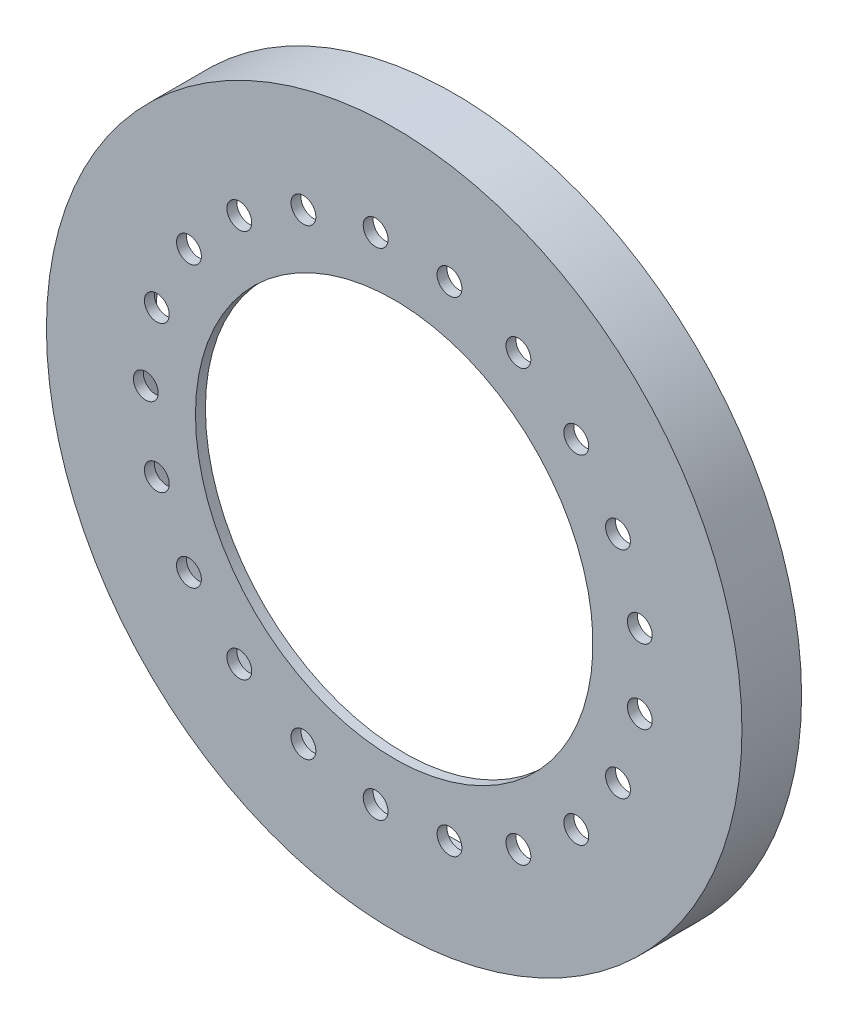
SolidWorks part; units mm, degrees
ref_plane "Front Plane" through (0, 0, 0) normal (0, 0, 1) x (1, 0, 0)
ref_plane "Top Plane" through (0, 0, 0) normal (0, 1, 0) x (1, 0, 0)
ref_plane "Right Plane" through (0, 0, 0) normal (1, 0, 0) x (0, 0, -1)
sketch "Sketch1" plane through (0, 0, 0) normal (0, 0, 1) x (1, 0, 0)
  circle A1 centre (0, 0) radius 76.2
  circle A2 centre (0, 0) radius 50.8
  point P50 (0, 0)
  dimension "D2" = 152.4
  dimension "D3" = 25.4
sketch "Sketch3" plane through (0, 0, 0) normal (0, 0, 1) x (1, 0, 0)
  circle A0 centre (0, 0) radius 88.9
  dimension "D1" = 177.8
extrude "Boss-Extrude2" add sketch "Sketch3" along normal blind 15.24
extrude "Cut-Extrude1" cut sketch "Sketch1" along normal blind 12.7
sketch "Sketch4" plane through (0, 0, 0) normal (0, 0, 1) x (1, 0, 0)
  line L0 (0, 0) -> (-63.5, 0) construction
  circle A0 centre (-63.5, 0) radius 3.175
  circle A21 centre (0, 0) radius 50.8
  circle A22 centre (-60.6789, 18.717) radius 3.175
  circle A23 centre (-52.4662, 35.7708) radius 3.175
  circle A24 centre (-39.5916, 49.6463) radius 3.175
  circle A25 centre (-23.1992, 59.1105) radius 3.175
  circle A26 centre (-4.7454, 63.3224) radius 3.175
  circle A27 centre (14.1301, 61.9079) radius 3.175
  circle A28 centre (31.75, 54.9926) radius 3.175
  circle A29 centre (46.5488, 43.191) radius 3.175
  circle A30 centre (57.2115, 27.5516) radius 3.175
  circle A31 centre (62.7908, 9.4642) radius 3.175
  circle A32 centre (62.7908, -9.4642) radius 3.175
  circle A33 centre (57.2115, -27.5516) radius 3.175
  circle A34 centre (46.5488, -43.191) radius 3.175
  circle A35 centre (31.75, -54.9926) radius 3.175
  circle A36 centre (14.1301, -61.9079) radius 3.175
  circle A37 centre (-4.7454, -63.3224) radius 3.175
  circle A38 centre (-23.1992, -59.1105) radius 3.175
  circle A39 centre (-39.5916, -49.6463) radius 3.175
  circle A40 centre (-52.4662, -35.7708) radius 3.175
  circle A41 centre (-60.6789, -18.717) radius 3.175
  point P45 (18.4232, -2.7769)
  point P49 (0, 0)
  dimension "D1" = 6.35
  dimension "D4" = 101.6
  dimension "D2" = 21
  dimension "D5" = 63.5
extrude "Cut-Extrude3" cut sketch "Sketch4" along normal through all
